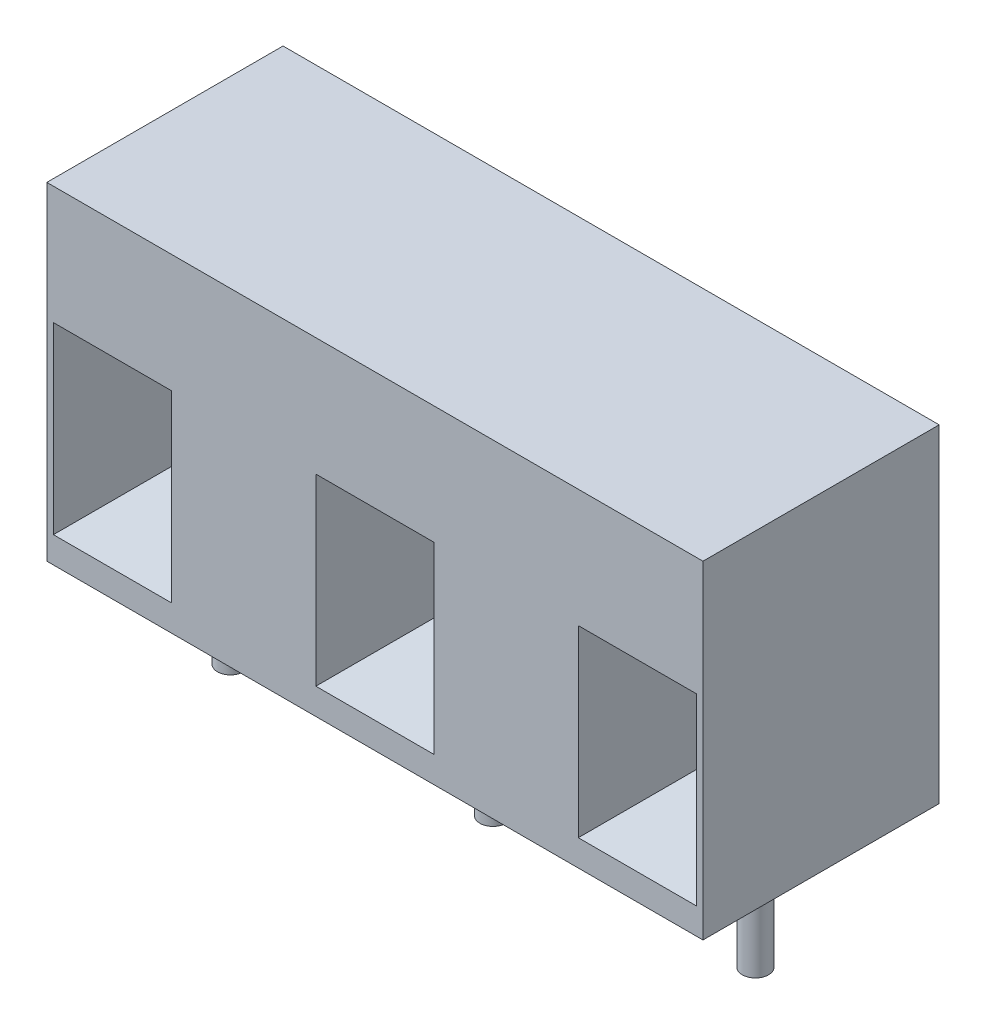
SolidWorks part; units mm, degrees
ref_plane "Front Plane" through (0, 0, 0) normal (0, 0, 1) x (1, 0, 0)
ref_plane "Top Plane" through (0, 0, 0) normal (0, 1, 0) x (1, 0, 0)
ref_plane "Right Plane" through (0, 0, 0) normal (1, 0, 0) x (0, 0, -1)
sketch "Sketch1" plane through (0, 0, 0) normal (0, 1, 0) x (1, 0, 0)
  line L1 (-12.5, -4.5) -> (12.5, -4.5)
  line L2 (-12.5, -4.5) -> (-12.5, 4.5)
  line L3 (-12.5, 4.5) -> (12.5, 4.5)
  line L4 (12.5, -4.5) -> (12.5, 4.5)
  line L5 (-12.5, -4.5) -> (12.5, 4.5) construction
  line L6 (-12.5, 4.5) -> (12.5, -4.5) construction
  point P0 (0, 0)
  dimension "D1" = 25
  dimension "D2" = 9
extrude "Boss-Extrude1" add sketch "Sketch1" along normal blind 12.5
sketch "Sketch2" plane through (0, 0, 0) normal (0, -1, 0) x (1, 0, 0)
  circle A0 centre (0, 0) radius 0.5
  circle A1 centre (-10, 0) radius 0.5
  circle A2 centre (10, 0) radius 0.5
  dimension "D1" = 1
  dimension "D2" = 10
  dimension "D3" = 10
extrude "Boss-Extrude2" add sketch "Sketch2" along normal blind 4.4
sketch "Sketch3" plane through (0, 0, 4.5) normal (0, 0, 1) x (1, 0, 0)
  line L0 (0, 0) -> (0, 12.5) construction
  line L1 (-12.5, 12.5) -> (12.5, 12.5) construction
  line L2 (-12.5, 4.5) -> (12.5, 4.5) construction
  line L5 (-10, 5.8838) -> (-10, 3.1162) construction
  line L6 (-2.25, 1) -> (2.25, 1)
  line L7 (-2.25, 1) -> (-2.25, 8)
  line L8 (-2.25, 8) -> (2.25, 8)
  line L9 (2.25, 1) -> (2.25, 8)
  line L10 (-2.25, 1) -> (2.25, 8) construction
  line L11 (-2.25, 8) -> (2.25, 1) construction
  line L12 (10, 6.6782) -> (10, 2.3218) construction
  line L13 (-12.5, 0) -> (12.5, 0) construction
  line L14 (7.75, 1) -> (12.25, 1)
  line L15 (7.75, 1) -> (7.75, 8)
  line L16 (7.75, 8) -> (12.25, 8)
  line L17 (12.25, 1) -> (12.25, 8)
  line L18 (7.75, 1) -> (12.25, 8) construction
  line L19 (7.75, 8) -> (12.25, 1) construction
  line L20 (-12.25, 1) -> (-7.75, 1)
  line L21 (-12.25, 1) -> (-12.25, 8)
  line L22 (-12.25, 8) -> (-7.75, 8)
  line L23 (-7.75, 1) -> (-7.75, 8)
  line L24 (-12.25, 1) -> (-7.75, 8) construction
  line L25 (-12.25, 8) -> (-7.75, 1) construction
  point P11 (0, 4.5)
  point P20 (-10, 4.5)
  point P21 (10, 4.5)
  point P22 (10, 4.5)
  point P27 (-10, 4.5)
  dimension "D1" = 4.5
  dimension "D2" = 7
  dimension "D3" = 10
  dimension "D4" = 10
  dimension "D5" = 4.5
extrude "Cut-Extrude1" cut sketch "Sketch3" against normal blind 4.4 draft 15
